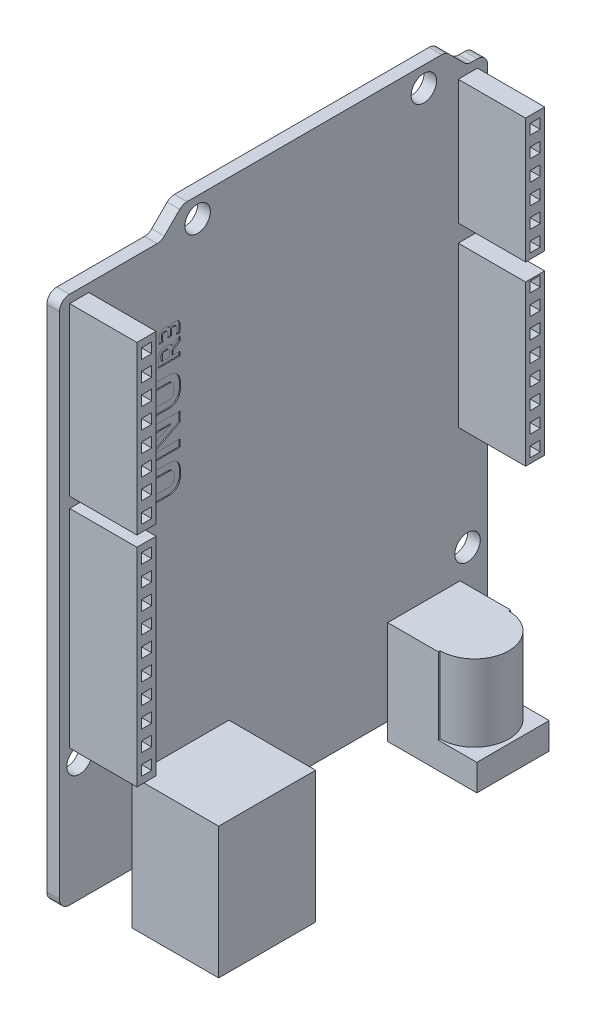
SolidWorks part; units mm, degrees
ref_plane "Front" through (0, 0, 0) normal (0, 0, 1) x (1, 0, 0)
ref_plane "Top" through (0, 0, 0) normal (0, 1, 0) x (1, 0, 0)
ref_plane "Right" through (0, 0, 0) normal (1, 0, 0) x (0, 0, -1)
sketch "Sketch1" plane through (0, 0, 0) normal (1, 0, 0) x (0, 0, -1)
  line L0 (-25.4, 29.3805) -> (-14.4961, 29.3805)
  line L1 (-10.7769, 32.0475) -> (20.9369, 32.0475)
  line L2 (-26.67, 28.1105) -> (-26.67, -35.2625)
  line L3 (-25.4, -36.5325) -> (25.4, -36.5325)
  line L4 (26.67, 28.1105) -> (26.67, -35.2625)
  line L5 (-21.4488, 29.3805) -> (26.67, -36.5325) construction
  line L6 (-26.67, -36.5325) -> (22.5802, 30.9303) construction
  line L7 (-13.598, 29.7524) -> (-11.675, 31.6755)
  line L8 (25.4, 29.3805) -> (24.6561, 29.3805)
  line L9 (23.758, 29.7524) -> (21.835, 31.6755)
  circle A0 centre (18.7325, 29.5456) radius 1.5875
  circle A1 centre (-9.4615, 29.5456) radius 1.5875
  circle A2 centre (24.1681, -22.7022) radius 1.5875
  circle A3 centre (-24.1681, -21.4322) radius 1.5875
  arc A4 (-26.67, -35.2625) -> (-25.4, -36.5325) centre (-25.4, -35.2625) ccw
  arc A5 (25.4, -36.5325) -> (26.67, -35.2625) centre (25.4, -35.2625) ccw
  arc A6 (25.4, 29.3805) -> (26.67, 28.1105) centre (25.4, 28.1105) cw
  arc A7 (21.835, 31.6755) -> (20.9369, 32.0475) centre (20.9369, 30.7775) ccw
  arc A8 (24.6561, 29.3805) -> (23.758, 29.7524) centre (24.6561, 30.6505) cw
  arc A9 (-11.675, 31.6755) -> (-10.7769, 32.0475) centre (-10.7769, 30.7775) cw
  arc A10 (-14.4961, 29.3805) -> (-13.598, 29.7524) centre (-14.4961, 30.6505) ccw
  arc A11 (-25.4, 29.3805) -> (-26.67, 28.1105) centre (-25.4, 28.1105) ccw
  point P0 (0, 0)
  point P28 (26.67, 29.3805)
  point P33 (24.13, 29.3805)
  point P38 (-13.97, 29.3805)
  point P41 (-26.67, 29.3805)
  dimension "D8" = 3.175
  dimension "D9" = 6.35
  dimension "D10" = 25.019
  dimension "D11" = 12.2428
  dimension "D12" = 13.5128
  dimension "D13" = 0.9144
  dimension "D14" = 0.9144
  dimension "D17" = 0.9144
  dimension "D18" = 1.27
  dimension "D1" = 68.58
  dimension "D2" = 53.34
  dimension "D3" = 12.7
  dimension "D4" = 45
  dimension "D5" = 2.667
  dimension "D6" = 45
  dimension "D7" = 2.54
  dimension "D15" = 36.5325
  dimension "D16" = 26.67
extrude "Boss-Extrude1" add sketch "Sketch1" along normal blind 1.5748
sketch "Sketch2" plane through (1.5748, 0, 0) normal (1, 0, 0) x (0, 0, -1)
  line L0 (-26.67, 28.1105) -> (-26.67, -35.2625) construction
  line L1 (-25.4, 28.3645) -> (-23.0124, 28.3645)
  line L2 (-25.4, 28.3645) -> (-25.4, 7.5873)
  line L3 (-25.4, 7.5873) -> (-23.0124, 7.5873)
  line L4 (-23.0124, 28.3645) -> (-23.0124, 7.5873)
  line L5 (-25.4, 28.3645) -> (-23.0124, 7.5873) construction
  line L6 (-25.4, 7.5873) -> (-23.0124, 28.3645) construction
  line L7 (-14.4961, 29.3805) -> (-25.4, 29.3805) construction
  line L8 (-24.8412, 24.9609) -> (-23.5712, 24.9609)
  line L9 (-24.8412, 27.5009) -> (-23.5712, 27.5009)
  line L10 (-24.8412, 27.5009) -> (-24.8412, 26.2309)
  line L11 (-24.8412, 26.2309) -> (-23.5712, 26.2309)
  line L12 (-23.5712, 27.5009) -> (-23.5712, 26.2309)
  line L13 (-24.8412, 27.5009) -> (-23.5712, 26.2309) construction
  line L14 (-24.8412, 26.2309) -> (-23.5712, 27.5009) construction
  line L15 (-24.8412, 24.9609) -> (-24.8412, 23.6909)
  line L16 (-24.8412, 23.6909) -> (-23.5712, 23.6909)
  line L17 (-23.5712, 24.9609) -> (-23.5712, 23.6909)
  line L18 (-24.8412, 24.9609) -> (-23.5712, 23.6909) construction
  line L19 (-24.8412, 23.6909) -> (-23.5712, 24.9609) construction
  line L20 (-24.8412, 22.4209) -> (-23.5712, 22.4209)
  line L21 (-24.8412, 22.4209) -> (-24.8412, 21.1509)
  line L22 (-24.8412, 21.1509) -> (-23.5712, 21.1509)
  line L23 (-23.5712, 22.4209) -> (-23.5712, 21.1509)
  line L24 (-24.8412, 22.4209) -> (-23.5712, 21.1509) construction
  line L25 (-24.8412, 21.1509) -> (-23.5712, 22.4209) construction
  line L26 (-24.8412, 19.8809) -> (-23.5712, 19.8809)
  line L27 (-24.8412, 19.8809) -> (-24.8412, 18.6109)
  line L28 (-24.8412, 18.6109) -> (-23.5712, 18.6109)
  line L29 (-23.5712, 19.8809) -> (-23.5712, 18.6109)
  line L30 (-24.8412, 19.8809) -> (-23.5712, 18.6109) construction
  line L31 (-24.8412, 18.6109) -> (-23.5712, 19.8809) construction
  line L32 (-24.8412, 17.3409) -> (-23.5712, 17.3409)
  line L33 (-24.8412, 17.3409) -> (-24.8412, 16.0709)
  line L34 (-24.8412, 16.0709) -> (-23.5712, 16.0709)
  line L35 (-23.5712, 17.3409) -> (-23.5712, 16.0709)
  line L36 (-24.8412, 17.3409) -> (-23.5712, 16.0709) construction
  line L37 (-24.8412, 16.0709) -> (-23.5712, 17.3409) construction
  line L38 (-24.8412, 14.8009) -> (-23.5712, 14.8009)
  line L39 (-24.8412, 14.8009) -> (-24.8412, 13.5309)
  line L40 (-24.8412, 13.5309) -> (-23.5712, 13.5309)
  line L41 (-23.5712, 14.8009) -> (-23.5712, 13.5309)
  line L42 (-24.8412, 14.8009) -> (-23.5712, 13.5309) construction
  line L43 (-24.8412, 13.5309) -> (-23.5712, 14.8009) construction
  line L44 (-24.8412, 12.2609) -> (-23.5712, 12.2609)
  line L45 (-24.8412, 12.2609) -> (-24.8412, 10.9909)
  line L46 (-24.8412, 10.9909) -> (-23.5712, 10.9909)
  line L47 (-23.5712, 12.2609) -> (-23.5712, 10.9909)
  line L48 (-24.8412, 12.2609) -> (-23.5712, 10.9909) construction
  line L49 (-24.8412, 10.9909) -> (-23.5712, 12.2609) construction
  line L50 (-24.8412, 9.7209) -> (-23.5712, 9.7209)
  line L51 (-24.8412, 9.7209) -> (-24.8412, 8.4509)
  line L52 (-24.8412, 8.4509) -> (-23.5712, 8.4509)
  line L53 (-23.5712, 9.7209) -> (-23.5712, 8.4509)
  line L54 (-24.8412, 9.7209) -> (-23.5712, 8.4509) construction
  line L55 (-24.8412, 8.4509) -> (-23.5712, 9.7209) construction
  line L56 (23.0124, 28.3645) -> (25.4, 28.3645)
  line L57 (23.0124, 28.3645) -> (23.0124, 7.5873)
  line L58 (23.0124, 7.5873) -> (25.4, 7.5873)
  line L59 (25.4, 28.3645) -> (25.4, 7.5873)
  line L60 (23.5712, 24.9609) -> (24.8412, 24.9609)
  line L61 (23.5712, 27.5009) -> (24.8412, 27.5009)
  line L62 (23.5712, 27.5009) -> (23.5712, 26.2309)
  line L63 (23.5712, 26.2309) -> (24.8412, 26.2309)
  line L64 (24.8412, 27.5009) -> (24.8412, 26.2309)
  line L65 (23.5712, 24.9609) -> (23.5712, 23.6909)
  line L66 (23.5712, 23.6909) -> (24.8412, 23.6909)
  line L67 (24.8412, 24.9609) -> (24.8412, 23.6909)
  line L68 (23.5712, 22.4209) -> (24.8412, 22.4209)
  line L69 (23.5712, 22.4209) -> (23.5712, 21.1509)
  line L70 (23.5712, 21.1509) -> (24.8412, 21.1509)
  line L71 (24.8412, 22.4209) -> (24.8412, 21.1509)
  line L72 (23.5712, 19.8809) -> (24.8412, 19.8809)
  line L73 (23.5712, 19.8809) -> (23.5712, 18.6109)
  line L74 (23.5712, 18.6109) -> (24.8412, 18.6109)
  line L75 (24.8412, 19.8809) -> (24.8412, 18.6109)
  line L76 (23.5712, 17.3409) -> (24.8412, 17.3409)
  line L77 (23.5712, 17.3409) -> (23.5712, 16.0709)
  line L78 (23.5712, 16.0709) -> (24.8412, 16.0709)
  line L79 (24.8412, 17.3409) -> (24.8412, 16.0709)
  line L80 (23.5712, 14.8009) -> (24.8412, 14.8009)
  line L81 (23.5712, 14.8009) -> (23.5712, 13.5309)
  line L82 (23.5712, 13.5309) -> (24.8412, 13.5309)
  line L83 (24.8412, 14.8009) -> (24.8412, 13.5309)
  line L84 (23.5712, 12.2609) -> (24.8412, 12.2609)
  line L85 (23.5712, 12.2609) -> (23.5712, 10.9909)
  line L86 (23.5712, 10.9909) -> (24.8412, 10.9909)
  line L87 (24.8412, 12.2609) -> (24.8412, 10.9909)
  line L88 (23.5712, 9.7209) -> (24.8412, 9.7209)
  line L89 (23.5712, 9.7209) -> (23.5712, 8.4509)
  line L90 (23.5712, 8.4509) -> (24.8412, 8.4509)
  line L91 (24.8412, 9.7209) -> (24.8412, 8.4509)
  line L92 (23.0124, 28.3645) -> (25.4, 7.5873) construction
  line L93 (23.0124, 7.5873) -> (25.4, 28.3645) construction
  line L94 (23.5712, 27.5009) -> (24.8412, 26.2309) construction
  line L95 (23.5712, 26.2309) -> (24.8412, 27.5009) construction
  line L96 (23.5712, 24.9609) -> (24.8412, 23.6909) construction
  line L97 (23.5712, 23.6909) -> (24.8412, 24.9609) construction
  line L98 (23.5712, 22.4209) -> (24.8412, 21.1509) construction
  line L99 (23.5712, 21.1509) -> (24.8412, 22.4209) construction
  line L100 (23.5712, 19.8809) -> (24.8412, 18.6109) construction
  line L101 (23.5712, 18.6109) -> (24.8412, 19.8809) construction
  line L102 (23.5712, 17.3409) -> (24.8412, 16.0709) construction
  line L103 (23.5712, 16.0709) -> (24.8412, 17.3409) construction
  line L104 (23.5712, 14.8009) -> (24.8412, 13.5309) construction
  line L105 (23.5712, 13.5309) -> (24.8412, 14.8009) construction
  line L106 (23.5712, 12.2609) -> (24.8412, 10.9909) construction
  line L107 (23.5712, 10.9909) -> (24.8412, 12.2609) construction
  line L108 (23.5712, 9.7209) -> (24.8412, 8.4509) construction
  line L109 (23.5712, 8.4509) -> (24.8412, 9.7209) construction
  line L110 (26.67, -35.2625) -> (26.67, 28.1105) construction
  point P0 (-24.2062, 17.9759)
  point P9 (-24.2062, 26.8659)
  point P15 (24.2062, 17.9759)
  point P16 (-24.2062, 24.3259)
  point P21 (-24.2062, 21.7859)
  point P26 (-24.2062, 19.2459)
  point P31 (-24.2062, 16.7059)
  point P36 (-24.2062, 14.1659)
  point P41 (-24.2062, 11.6259)
  point P46 (-24.2062, 9.0859)
  point P55 (24.2062, 26.8659)
  point P60 (24.2062, 24.3259)
  point P65 (24.2062, 21.7859)
  point P70 (24.2062, 19.2459)
  point P75 (24.2062, 16.7059)
  point P80 (24.2062, 14.1659)
  point P85 (24.2062, 11.6259)
  point P90 (24.2062, 9.0859)
  dimension "D1" = 2.3876
  dimension "D2" = 20.7772
  dimension "D3" = 1.27
  dimension "D4" = 1.016
  dimension "D5" = 1.27
  dimension "D6" = 0.8636
  dimension "D8" = 0.8636
  dimension "D10" = 1.27
  dimension "D7" = 8
  dimension "D9" = 2
extrude "Boss-Extrude2" add sketch "Sketch2" along normal blind 8.382
pattern_linear "LPattern1" count 2 spacing 22.098 along (0, -1, 0) of "Boss-Extrude2"
sketch "Sketch3" plane through (0, -14.5107, 0) normal (0, -1, 0) x (1, 0, 0)
  line L4 (1.5748, 25.4) -> (1.5748, 23.0124)
  line L5 (1.5748, 23.0124) -> (9.9568, 23.0124)
  line L6 (9.9568, 23.0124) -> (9.9568, 25.4)
  line L7 (9.9568, 25.4) -> (1.5748, 25.4)
  line L8 (1.5748, 25.4) -> (1.5748, 23.0124)
  line L9 (1.5748, 23.0124) -> (9.9568, 23.0124)
  line L10 (9.9568, 23.0124) -> (9.9568, 25.4)
  line L11 (9.9568, 25.4) -> (1.5748, 25.4)
  dimension "D1" = 0
extrude "Boss-Extrude3" add sketch "Sketch3" along normal blind 5.08
sketch "Sketch4" plane through (9.9568, 0, 0) normal (1, 0, 0) x (0, 0, -1)
  line L0 (-23.5712, -13.6471) -> (-23.5712, -12.3771) construction
  line L1 (-24.8412, -14.9171) -> (-23.5712, -14.9171)
  line L2 (-24.8412, -14.9171) -> (-24.8412, -16.1871)
  line L3 (-24.8412, -16.1871) -> (-23.5712, -16.1871)
  line L4 (-23.5712, -14.9171) -> (-23.5712, -16.1871)
  line L5 (-24.8412, -14.9171) -> (-23.5712, -16.1871) construction
  line L6 (-24.8412, -16.1871) -> (-23.5712, -14.9171) construction
  line L7 (-24.8412, -12.3771) -> (-24.8412, -13.6471) construction
  line L8 (-24.8412, -13.6471) -> (-23.5712, -13.6471) construction
  line L9 (-24.8412, -17.4571) -> (-23.5712, -17.4571)
  line L10 (-24.8412, -17.4571) -> (-24.8412, -18.7271)
  line L11 (-24.8412, -18.7271) -> (-23.5712, -18.7271)
  line L12 (-23.5712, -17.4571) -> (-23.5712, -18.7271)
  point P0 (-24.2062, -15.5521)
  dimension "D1" = 1.27
  dimension "D2" = 1.27
  dimension "D3" = 2
extrude "Cut-Extrude1" cut sketch "Sketch4" against normal up to surface (8.382 mm away) up to face at (1.5748, -4.1221, -24.2062)
sketch "Sketch5" plane through (9.9568, 0, 0) normal (1, 0, 0) x (0, 0, -1)
  line L0 (25.4, 7.5873) -> (25.4, 28.3645) construction
  line L1 (23.0124, 12.84) -> (25.4, 12.84)
  line L2 (23.0124, 12.84) -> (23.0124, 7.5873)
  line L3 (23.0124, 7.5873) -> (25.4, 7.5873)
  line L4 (25.4, 12.84) -> (25.4, 7.5873)
  line L5 (23.0124, 12.84) -> (25.4, 7.5873) construction
  line L6 (23.0124, 7.5873) -> (25.4, 12.84) construction
  line L7 (23.0124, 28.3645) -> (23.0124, 7.5873) construction
  line L8 (23.0124, 7.5873) -> (25.4, 7.5873) construction
  line L9 (24.2062, 13.5309) -> (24.2062, 12.2609) construction
  line L10 (23.5712, 13.5309) -> (24.8412, 13.5309) construction
  line L11 (24.8412, 12.2609) -> (23.5712, 12.2609) construction
  point P0 (24.2062, 10.2136)
  point P17 (24.2062, 12.84)
extrude "Cut-Extrude2" cut sketch "Sketch5" against normal up to surface (8.382 mm away) up to face at (1.5748, -4.1221, -24.2062)
sketch "Sketch6" plane through (0, 6.2665, 0) normal (0, 1, 0) x (1, 0, 0)
  line L4 (1.5748, 25.4) -> (1.5748, 23.0124)
  line L5 (1.5748, 23.0124) -> (9.9568, 23.0124)
  line L6 (9.9568, 23.0124) -> (9.9568, 25.4)
  line L7 (9.9568, 25.4) -> (1.5748, 25.4)
  line L8 (1.5748, 25.4) -> (1.5748, 23.0124)
  line L9 (1.5748, 23.0124) -> (9.9568, 23.0124)
  line L10 (9.9568, 23.0124) -> (9.9568, 25.4)
  line L11 (9.9568, 25.4) -> (1.5748, 25.4)
  dimension "D1" = 0
extrude "Boss-Extrude4" add sketch "Sketch6" along normal offset from surface (4.4145 mm away) 2.159 up to face at (5.7658, 12.84, -24.2062)
sketch "Sketch7" plane through (9.9568, 0, 0) normal (1, 0, 0) x (0, 0, -1)
  line L1 (23.5712, 7.9429) -> (24.8412, 7.9429)
  line L2 (23.5712, 7.9429) -> (23.5712, 6.6729)
  line L3 (23.5712, 6.6729) -> (24.8412, 6.6729)
  line L4 (24.8412, 7.9429) -> (24.8412, 6.6729)
  line L5 (23.5712, 7.9429) -> (24.8412, 6.6729) construction
  line L6 (23.5712, 6.6729) -> (24.8412, 7.9429) construction
  line L7 (24.8412, 4.1329) -> (24.8412, 5.4029) construction
  line L8 (23.5712, 5.4029) -> (23.5712, 4.1329) construction
  line L9 (24.8412, 5.4029) -> (23.5712, 5.4029) construction
  line L12 (23.5712, 9.2129) -> (24.8412, 9.2129)
  line L13 (23.5712, 10.4829) -> (23.5712, 9.2129)
  line L14 (23.5712, 10.4829) -> (24.8412, 10.4829)
  line L15 (24.8412, 10.4829) -> (24.8412, 9.2129)
  point P0 (24.2062, 7.3079)
  dimension "D1" = 1.27
  dimension "D2" = 2
extrude "Cut-Extrude3" cut sketch "Sketch7" against normal up to surface (8.382 mm away) up to face at (1.5748, 4.7679, 24.2062)
sketch "Sketch8" plane through (9.9568, 0, 0) normal (1, 0, 0) x (0, 0, -1)
  line L0 (23.0124, 10.681) -> (23.0124, -14.5107) construction
  line L1 (23.0124, -9.2021) -> (25.4, -9.2021)
  line L2 (23.0124, -9.2021) -> (23.0124, -14.5107)
  line L3 (23.0124, -14.5107) -> (25.4, -14.5107)
  line L4 (25.4, -9.2021) -> (25.4, -14.5107)
  line L5 (23.0124, -9.2021) -> (25.4, -14.5107) construction
  line L6 (23.0124, -14.5107) -> (25.4, -9.2021) construction
  line L7 (23.0124, 10.681) -> (23.0124, -14.5107) construction
  line L8 (24.2062, -9.8371) -> (24.2062, -8.5671) construction
  line L9 (24.8412, -9.8371) -> (23.5712, -9.8371) construction
  line L10 (23.5712, -8.5671) -> (24.8412, -8.5671) construction
  point P0 (24.2062, -11.8564)
  point P6 (24.2062, -9.2021)
extrude "Cut-Extrude4" cut sketch "Sketch8" against normal up to surface (8.382 mm away) up to face at (1.5748, 4.7679, 24.2062)
sketch "Sketch9" plane through (0, -36.5325, 0) normal (0, -1, 0) x (1, 0, 0)
  line L0 (1.5748, 25.4) -> (1.5748, -25.4) construction
  line L1 (12.6746, -23.241) -> (1.5748, -23.241)
  line L2 (12.6746, -23.241) -> (12.6746, -14.224)
  line L3 (12.6746, -14.224) -> (1.5748, -14.224)
  line L4 (1.5748, -23.241) -> (1.5748, -14.224)
  line L5 (12.6746, -23.241) -> (1.5748, -14.224) construction
  line L6 (12.6746, -14.224) -> (1.5748, -23.241) construction
  line L7 (1.5748, -26.67) -> (0, -26.67) construction
  circle A0 centre (7.874, -18.7325) radius 3.175
  circle A1 centre (7.874, -18.7325) radius 0.635
  point P0 (7.1247, -18.7325)
  line M6 (1.5748, -25.4) -> (1.5748, 25.4)
  dimension "D4" = 6.35
  dimension "D5" = 1.6256
  dimension "D6" = 1.27
  dimension "D1" = 9.017
  dimension "D2" = 3.429
  dimension "D3" = 11.0998
extrude "Boss-Extrude5" add sketch "Sketch9" along normal blind 2.159 and the other way blind 1.143 contours L2 L3 L1 A0 M6 | A1
sketch "Sketch10" plane through (0, -35.3895, 0) normal (0, 1, 0) x (1, 0, 0)
  line L4 (12.6746, 14.224) -> (12.6746, 23.241)
  line L5 (12.6746, 23.241) -> (1.5748, 23.241)
  line L6 (1.5748, 23.241) -> (1.5748, 14.224)
  line L7 (1.5748, 14.224) -> (12.6746, 14.224)
  line L9 (7.874, 23.241) -> (1.5748, 23.241)
  line L10 (1.5748, 23.241) -> (1.5748, 14.224)
  line L11 (1.5748, 14.224) -> (7.874, 14.224)
  line L12 (7.874, 23.0124) -> (7.874, 23.241)
  line L13 (7.874, 14.4526) -> (7.874, 14.224)
  arc A2 (7.874, 14.4526) -> (7.874, 23.0124) centre (7.874, 18.7325) ccw
  dimension "D1" = 0
extrude "Boss-Extrude6" add sketch "Sketch10" along normal blind 9.525
sketch "Sketch11" plane through (0, -36.5325, 0) normal (0, -1, 0) x (1, 0, 0)
  line L0 (1.5748, 25.4) -> (1.5748, -14.224) construction
  line L1 (12.3698, 5.5626) -> (1.5748, 5.5626)
  line L2 (12.3698, 5.5626) -> (12.3698, 17.6276)
  line L3 (12.3698, 17.6276) -> (1.5748, 17.6276)
  line L4 (1.5748, 5.5626) -> (1.5748, 17.6276)
  line L5 (12.3698, 5.5626) -> (1.5748, 17.6276) construction
  line L6 (12.3698, 17.6276) -> (1.5748, 5.5626) construction
  point P0 (6.9723, 11.5951)
  dimension "D1" = 9.0424
  dimension "D2" = 12.065
  dimension "D3" = 10.795
extrude "Boss-Extrude7" add sketch "Sketch11" along normal blind 6.35 and the other way blind 10.033
sketch "Sketch12" plane through (0, -42.8825, 0) normal (0, -1, 0) x (1, 0, 0)
  line L0 (3.3528, 15.8496) -> (3.3528, 7.3406)
  line L1 (3.3528, 7.3406) -> (8.9408, 7.3406)
  line L2 (8.9408, 7.3406) -> (11.0998, 9.4996)
  line L3 (11.0998, 9.4996) -> (11.0998, 13.6906)
  line L4 (11.0998, 13.6906) -> (8.9408, 15.8496)
  line L5 (8.9408, 15.8496) -> (3.3528, 15.8496)
  line L6 (11.0998, 11.5951) -> (3.3528, 11.5951) construction
  line L7 (5.7023, 8.8011) -> (8.7503, 8.8011)
  line L8 (5.7023, 8.8011) -> (5.7023, 14.3891)
  line L9 (5.7023, 14.3891) -> (8.7503, 14.3891)
  line L10 (8.7503, 8.8011) -> (8.7503, 14.3891)
  line L11 (5.7023, 8.8011) -> (8.7503, 14.3891) construction
  line L12 (5.7023, 14.3891) -> (8.7503, 8.8011) construction
  line L13 (1.5748, 5.5626) -> (12.3698, 5.5626) construction
  line L14 (12.3698, 11.5951) -> (1.5748, 11.5951) construction
  line L15 (12.3698, 5.5626) -> (12.3698, 17.6276) construction
  line L16 (1.5748, 17.6276) -> (1.5748, 5.5626) construction
  point P2 (7.2263, 11.5951)
  point P13 (7.2263, 11.5951)
  dimension "D1" = 1.778
  dimension "D2" = 1.778
  dimension "D3" = 1.27
  dimension "D4" = 45
  dimension "D5" = 5.588
  dimension "D6" = 3.048
  dimension "D7" = 5.588
extrude "Cut-Extrude5" cut sketch "Sketch12" against normal blind 9.144
sketch "Sketch13" plane through (1.5748, 0, 0) normal (1, 0, 0) x (0, 0, -1)
  line L0 (-11.5951, -26.4995) -> (-11.675, 31.6755) construction
  line L1 (-17.6276, -26.4995) -> (-5.5626, -26.4995) construction
  text T0 "        UNO " font "Times New Roman" height in points 18
  text T1 "                                    R3" font "Times New Roman" height in points 10
extrude "Cut-Extrude6" cut sketch "Sketch13" against normal blind 0.127
